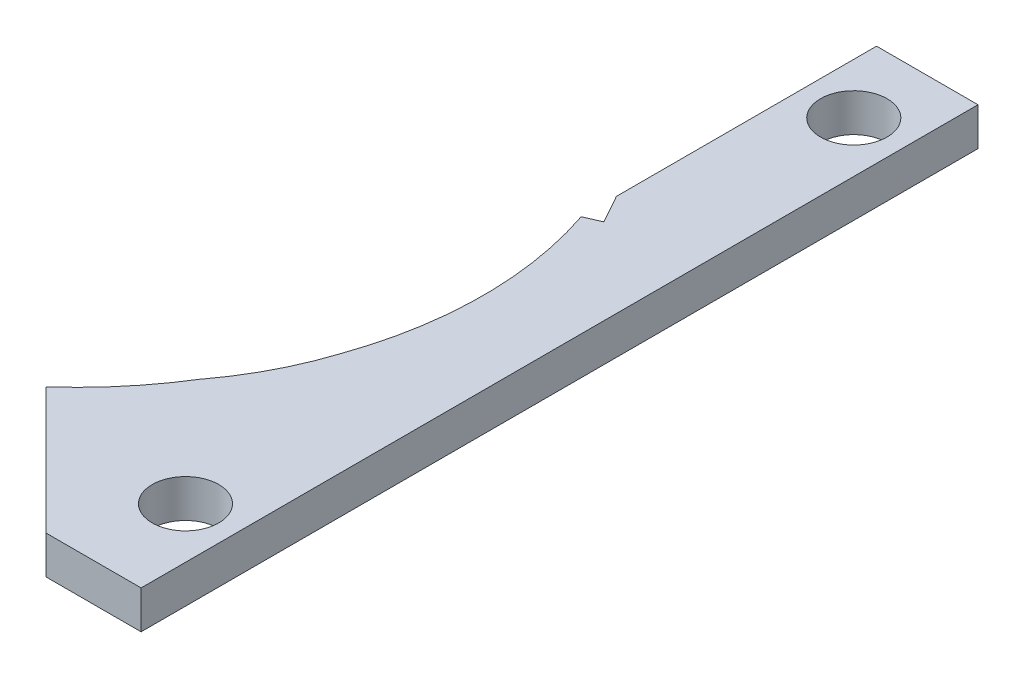
SolidWorks part; units mm, degrees
ref_plane "Front Plane" through (0, 0, 0) normal (0, 0, 1) x (1, 0, 0)
ref_plane "Top Plane" through (0, 0, 0) normal (0, 1, 0) x (1, 0, 0)
ref_plane "Right Plane" through (0, 0, 0) normal (1, 0, 0) x (0, 0, -1)
sketch "Model" plane through (0, 0, 0) normal (0, -1, 0) x (1, 0, 0)
  line L0 (694.5, -169.7999) -> (697, -170.9)
  line L1 (697, -170.9) -> (694.5, -175.3706)
  line L2 (694.5, -175.3706) -> (694.5, -216.4)
  line L3 (694.5, -216.4) -> (710.5, -216.4)
  line L4 (710.5, -216.4) -> (710.5, -84.4)
  line L5 (710.5, -84.4) -> (695.5, -84.4)
  line L6 (695.5, -84.4) -> (695.5, -89.4)
  circle A0 centre (702.5, -204.8085) radius 5.25
  circle A1 centre (702.5, -99.4) radius 5.25
  arc A2 (685.9185, -116.6194) -> (695.5, -89.4) centre (647.6231, -87.8429) ccw
  arc A3 (694.2363, -132.1516) -> (685.9185, -116.6194) centre (647.683, -147.0889) ccw
  arc A4 (694.5, -169.7999) -> (694.2363, -132.1516) centre (639.98, -151.3566) ccw
extrude "Boss-Extrude1" add sketch "Model" along normal blind 6
sketch "Sketch2" plane through (0, 0, 0) normal (0, 1, 0) x (1, 0, 0)
  line L0 (695.5, 84.4) -> (675.5298, 104.3702)
  line L1 (697.0455, 96.9132) -> (686.8, 117.8029)
  line L5 (695.5, 84.4) -> (697.0455, 96.9132)
  circle A3 centre (702.5, 99.4) radius 5.25 construction
  arc A5 (675.5298, 104.3702) -> (686.8, 117.8029) centre (635.5, 149.4) ccw
  dimension "D1" = 67
  dimension "D2" = 50
extrude "Boss-Extrude2" add sketch "Sketch2" against normal blind 6
sketch "Sketch3" plane through (0, 0, 0) normal (0, 1, 0) x (1, 0, 0)
  circle A0 centre (635.5, 149.4) radius 60.25
extrude "Cut-Extrude1" cut sketch "Sketch3" against normal blind 10
